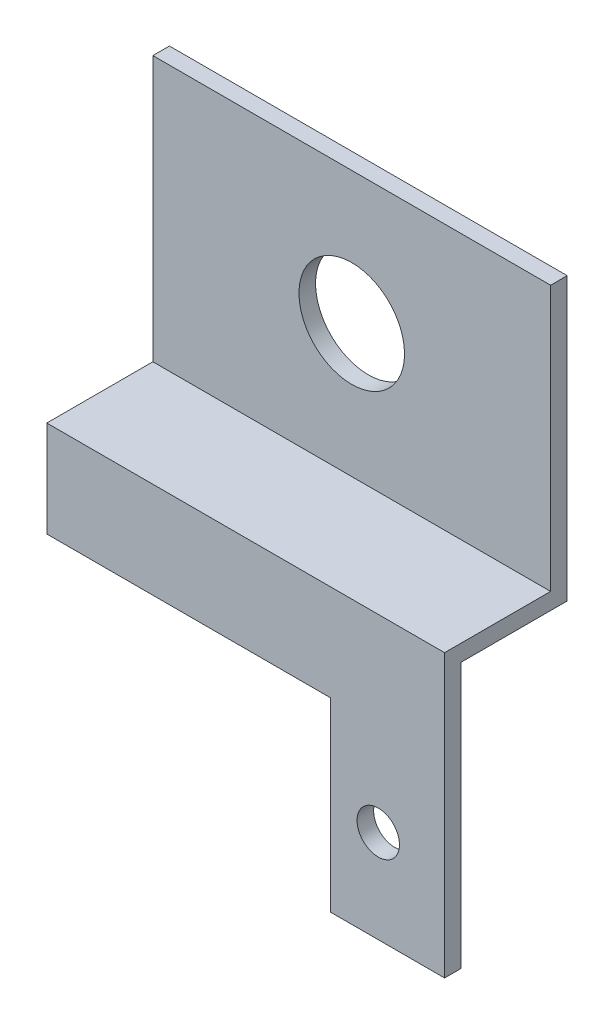
SolidWorks part; units mm, degrees
material "Plain Carbon Steel"
ref_plane "Front Plane" through (0, 0, 0) normal (0, 0, 1) x (1, 0, 0)
ref_plane "Top Plane" through (0, 0, 0) normal (0, 1, 0) x (1, 0, 0)
ref_plane "Right Plane" through (0, 0, 0) normal (1, 0, 0) x (0, 0, -1)
sketch "Sketch1" plane through (0, 0, 0) normal (1, 0, 0) x (0, 0, -1)
  line L0 (-14.9803, -13.4938) -> (-14.9803, 0)
  line L1 (-14.9803, 0) -> (-9.9003, 0)
  line L2 (-9.9003, 0) -> (-9.9003, 12.7)
  line L3 (-9.9003, 12.7) -> (-9.1066, 12.7)
  line L4 (-9.1066, 12.7) -> (-9.1066, -0.7938)
  line L5 (-9.1066, -0.7938) -> (-14.1866, -0.7938)
  line L6 (-14.1866, -0.7938) -> (-14.1866, -13.4938)
  line L7 (-14.1866, -13.4938) -> (-14.9803, -13.4938)
  dimension "D1" = 0.7937
  dimension "D2" = 0.7937
  dimension "D3" = 0.7937
  dimension "D4" = 12.7
  dimension "D5" = 5.08
  dimension "D6" = 12.7
extrude "Boss-Extrude1" add sketch "Sketch1" along normal blind 19.05
hole_wizard "#8 (0.199) Diameter Hole1" positions "3DSketch1" profile "Sketch3" hole size "#8" standard "ANSI Inch" end condition through all
sketch3d "3DSketch1"
  line L0 (19.05, 12.7, 9.9003) -> (0, 12.7, 9.9003) construction
  line L1 (19.05, 12.7, 9.9003) -> (19.05, 0, 9.9003) construction
  line L2 (19.05, 0, 9.9003) -> (0, 0, 9.9003) construction
  line L3 (19.05, 0, 9.9003) -> (0, 0, 9.9003)
  point P0 (9.525, 6.35, 9.9003)
  dimension "D1" = 6.35
  dimension "D2" = 9.525
  dimension "D3" = 12.7
sketch "Sketch3" plane through (9.525, 6.35, 9.9003) normal (1, 0, 0) x (0, -1, 0)
  line L0 (0, 0) -> (0, 0.7938)
  line L1 (0, 0.7938) -> (2.5273, 0.7938)
  line L2 (2.5273, 0.7938) -> (2.5273, 0)
  line L5 (2.5273, 0) -> (0, 0)
  line L11 (0, -6.35) -> (0, 107.95) construction
  dimension "Thru Hole Dia." = 5.0546
  dimension "Thru Hole Depth" = 0.7938
sketch "Sketch4" plane through (0, 0, 14.1866) normal (0, 0, -1) x (-1, 0, 0)
  line L1 (0, -13.4937) -> (-13.589, -13.4937)
  line L2 (0, -13.4937) -> (0, -4.6037)
  line L3 (0, -4.6037) -> (-13.589, -4.6038)
  line L4 (0, -13.4937) -> (0, -0.7937)
  line L5 (0, -0.7937) -> (-19.05, -0.7937)
  line L6 (-19.05, -0.7937) -> (-19.05, -13.4937)
  line L7 (-19.05, -13.4937) -> (0, -13.4937)
  line L8 (0, -13.4937) -> (0, -0.7937)
  line L9 (0, -0.7937) -> (-19.05, -0.7937)
  line L10 (-19.05, -0.7937) -> (-19.05, -13.4937)
  line L11 (-19.05, -13.4937) -> (0, -13.4937)
  line L12 (-13.589, -13.4937) -> (-13.589, -4.6038)
  circle A0 centre (-15.875, -9.0488) radius 1.016
  line M5 (0, -13.4937) -> (0, -0.7937)
  line M8 (-19.05, -13.4937) -> (0, -13.4937)
  dimension "D3" = 2.032
  dimension "D2" = 4.445
  dimension "D4" = 3.175
  dimension "D5" = 2.286
  dimension "D6" = 8.89
  dimension "D1" = 0
extrude "Cut-Extrude1" cut sketch "Sketch4" against normal through all contours A0 | L12 L3 M8 M5
equation "\"D1@3DSketch1\"=\"D3@3DSketch1\"/2"
